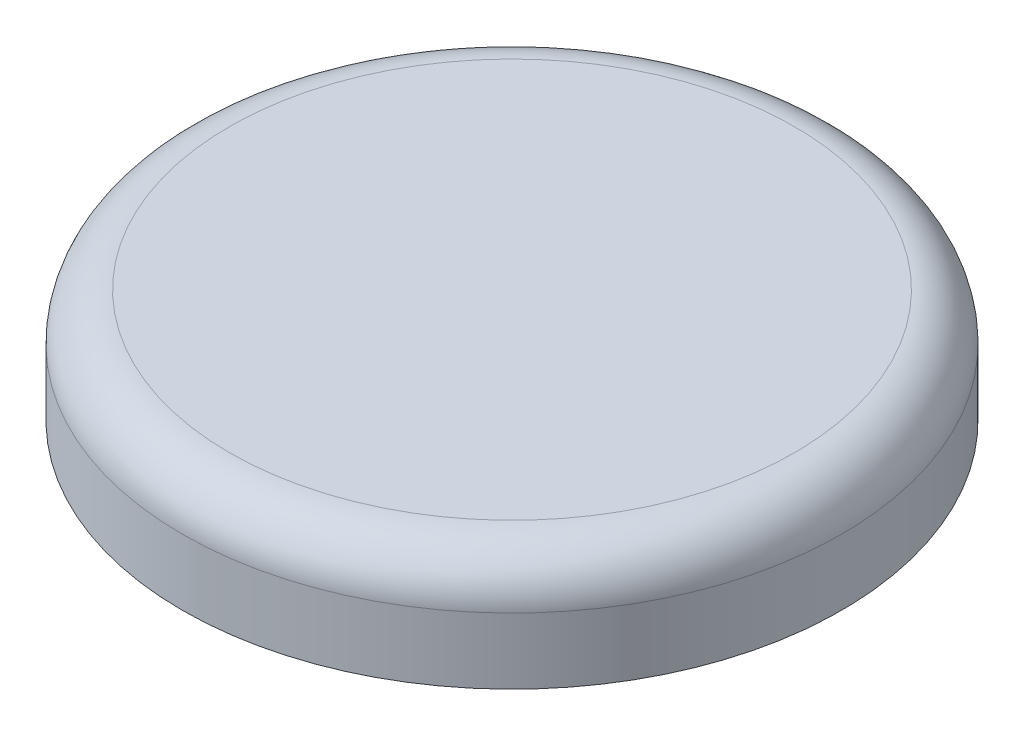
SolidWorks part; units mm, degrees
material "ABS"
ref_plane "前视基准面" through (0, 0, 0) normal (0, 0, 1) x (1, 0, 0)
ref_plane "上视基准面" through (0, 0, 0) normal (0, 1, 0) x (1, 0, 0)
ref_plane "右视基准面" through (0, 0, 0) normal (1, 0, 0) x (0, 0, -1)
sketch "草图1" plane through (0, 0, 0) normal (0, 1, 0) x (1, 0, 0)
  circle A0 centre (0, 0) radius 35
  dimension "D1" = 70
extrude "凸台-拉伸1" add sketch "草图1" along normal blind 12
sketch "草图2" plane through (0, 0, 0) normal (0, -1, 0) x (1, 0, 0)
  line L0 (-35, 0) -> (35, 0) construction
  line L1 (0, 35) -> (0, -35) construction
  line L2 (-18.2, -27.2509) -> (-14.5, -29.3871)
  line L3 (32.7, -2.1362) -> (32.7, 2.1362)
  line L4 (32.7, 2.1362) -> (29, 4.2724)
  line L5 (29, 4.2724) -> (25.3, 2.1362)
  line L6 (25.3, 2.1362) -> (25.3, -2.1362)
  line L7 (25.3, -2.1362) -> (29, -4.2724)
  line L8 (29, -4.2724) -> (32.7, -2.1362)
  line L9 (-14.5, -29.3871) -> (-10.8, -27.2509)
  line L10 (-10.8, -27.2509) -> (-10.8, -22.9785)
  line L11 (-10.8, -22.9785) -> (-14.5, -20.8423)
  line L12 (-14.5, -20.8423) -> (-18.2, -22.9785)
  line L13 (-18.2, -22.9785) -> (-18.2, -27.2509)
  line L14 (-14.5, 29.3871) -> (-18.2, 27.2509)
  line L15 (-18.2, 27.2509) -> (-18.2, 22.9785)
  line L16 (-18.2, 22.9785) -> (-14.5, 20.8423)
  line L17 (-14.5, 20.8423) -> (-10.8, 22.9785)
  line L18 (-10.8, 22.9785) -> (-10.8, 27.2509)
  line L19 (-10.8, 27.2509) -> (-14.5, 29.3871)
  circle A0 centre (0, 0) radius 35 construction
  circle A1 centre (0, 0) radius 29 construction
  circle A2 centre (29, 0) radius 3.7 construction
  circle A3 centre (-14.5, -25.1147) radius 3.7 construction
  circle A4 centre (-14.5, 25.1147) radius 3.7 construction
  dimension "D1" = 58
  dimension "D2" = 7.4
  dimension "D3" = 3
extrude "切除-拉伸1" cut sketch "草图2" against normal blind 4
sketch "草图3" plane through (0, 4, 0) normal (0, -1, 0) x (1, 0, 0)
  line L0 (29, 4.2724) -> (29, -4.2724) construction
  line L1 (29, -4.2724) -> (32.7, -2.1362) construction
  line L2 (29, -4.2724) -> (32.7, -2.1362) construction
  line L3 (25.3, 2.1362) -> (32.7, -2.1362) construction
  line L4 (32.7, 2.1362) -> (25.3, -2.1362) construction
  line L5 (0, 35) -> (0, -35) construction
  circle A0 centre (29, 0) radius 2
  circle A1 centre (0, 0) radius 35 construction
  circle A2 centre (-14.5, -25.1147) radius 2
  circle A3 centre (-14.5, 25.1147) radius 2
  dimension "D1" = 4
  dimension "D2" = 3
extrude "切除-拉伸2" cut sketch "草图3" against normal blind 5
fillet "圆角1" radius 5 1 edges at (0, 12, 35)
sketch "草图4" plane through (0, 0, 0) normal (0, -1, 0) x (1, 0, 0)
  circle A0 centre (0, 0) radius 20
  dimension "D1" = 40
extrude "切除-拉伸3" cut sketch "草图4" against normal blind 10
fillet "圆角2" radius 5 1 edges at (0, 10, -20)
sketch "草图5" plane through (0, 0, 0) normal (0, -1, 0) x (1, 0, 0)
  circle A0 centre (0, 0) radius 23.6
  dimension "D1" = 47.2
extrude "切除-拉伸4" cut sketch "草图5" against normal blind 2.3
